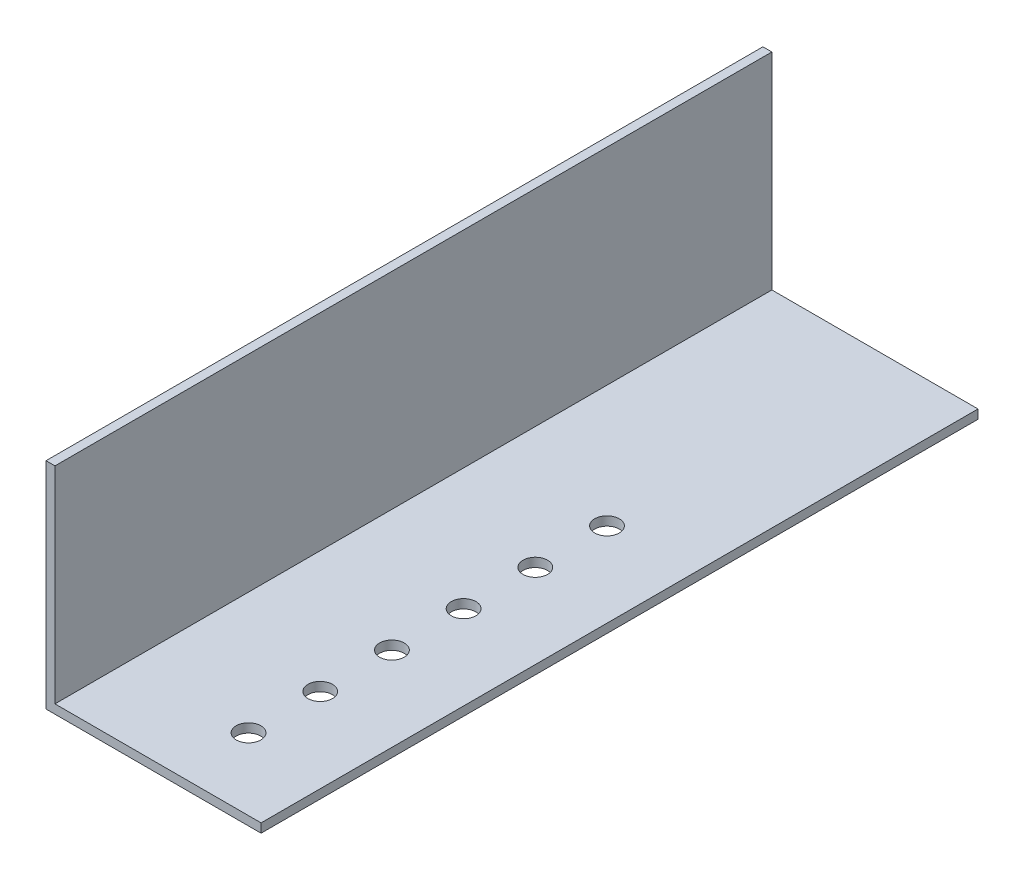
SolidWorks part; units mm, degrees
ref_plane "Front Plane" through (0, 0, 0) normal (0, 0, 1) x (1, 0, 0)
ref_plane "Top Plane" through (0, 0, 0) normal (0, 1, 0) x (1, 0, 0)
ref_plane "Right Plane" through (0, 0, 0) normal (1, 0, 0) x (0, 0, -1)
sketch "Sketch1" plane through (0, 0, 0) normal (0, 0, 1) x (1, 0, 0)
  line L0 (0, 0) -> (0, 38.1)
  line L1 (0, 38.1) -> (1.5875, 38.1)
  line L2 (1.5875, 38.1) -> (1.5875, 1.5875)
  line L3 (1.5875, 1.5875) -> (38.1, 1.5875)
  line L4 (38.1, 1.5875) -> (38.1, 0)
  line L5 (38.1, 0) -> (0, 0)
  dimension "D1" = 38.1
  dimension "D2" = 1.5875
extrude "Boss-Extrude1" add sketch "Sketch1" along normal blind 127
sketch "Sketch2" plane through (0, 1.5875, 0) normal (0, 1, 0) x (1, 0, 0)
  line L0 (23.1775, -127) -> (23.1775, 0) construction
  line L1 (38.1, -127) -> (1.5875, -127) construction
  line L3 (1.5875, -127) -> (1.5875, 0) construction
  circle A0 centre (23.1775, -114.3) radius 2.1828
  circle A1 centre (23.1775, -101.6) radius 2.1828
  circle A2 centre (23.1775, -88.9) radius 2.1828
  circle A3 centre (23.1775, -76.2) radius 2.1828
  circle A4 centre (23.1775, -63.5) radius 2.1828
  circle A5 centre (23.1775, -50.8) radius 2.1828
  point P18 (0, 0)
  dimension "D1" = 4.3656
  dimension "D2" = 12.7
  dimension "D5" = 12.7
  dimension "D6" = 12.7
  dimension "D7" = 12.7
  dimension "D3" = 12.7
  dimension "D4" = 12.7
  dimension "D8" = 21.59
extrude "Cut-Extrude1" cut sketch "Sketch2" against normal blind 127
